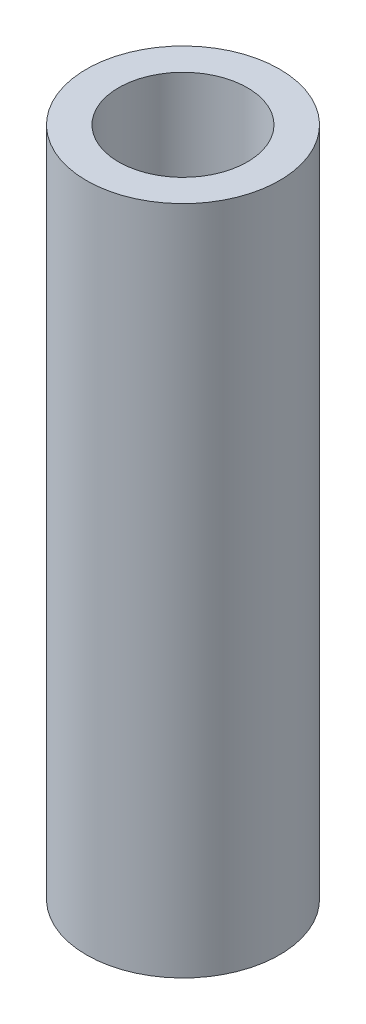
SolidWorks part; units mm, degrees
ref_plane "Front Plane" through (0, 0, 0) normal (0, 0, 1) x (1, 0, 0)
ref_plane "Top Plane" through (0, 0, 0) normal (0, 1, 0) x (1, 0, 0)
ref_plane "Right Plane" through (0, 0, 0) normal (1, 0, 0) x (0, 0, -1)
sketch "Sketch1" plane through (0, 0, 0) normal (0, 1, 0) x (1, 0, 0)
  circle A0 centre (0, 0) radius 4
  circle A1 centre (0, 0) radius 6
  dimension "D1" = 8
  dimension "D2" = 2
extrude "Boss-Extrude1" add sketch "Sketch1" along normal blind 41.67
